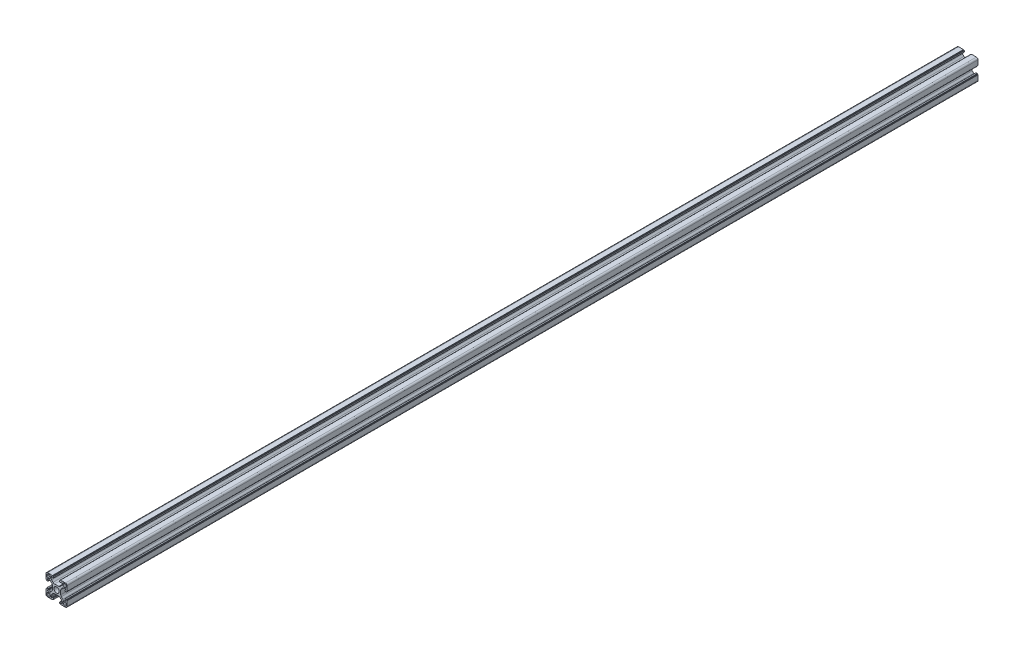
SolidWorks part; units mm, degrees
material "1060 Сплав"
ref_plane "Спереди" through (0, 0, 0) normal (0, 0, 1) x (1, 0, 0)
ref_plane "Сверху" through (0, 0, 0) normal (0, 1, 0) x (1, 0, 0)
ref_plane "Справа" through (0, 0, 0) normal (1, 0, 0) x (0, 0, -1)
sketch "Эскиз2" plane through (0, 0, 0) normal (0, 0, 1) x (1, 0, 0)
  line L0 (9.2299, 9.7837) -> (6.2299, 6.7837) construction
  line L1 (0.1299, 4.6837) -> (2.0286, 4.6837)
  line L2 (0.1299, 0.6837) -> (10.1299, 10.6837) construction
  line L3 (7.7299, 8.2837) -> (6.2299, 9.7837) construction
  line L4 (3.4428, 5.2695) -> (4.7441, 6.5707)
  line L5 (7.0299, 6.7837) -> (8.4299, 6.7837)
  line L6 (6.2299, 7.5837) -> (6.2299, 8.9837)
  line L7 (8.4299, 9.7837) -> (7.0299, 9.7837)
  line L8 (5.3299, 8.8837) -> (5.3299, 7.9849)
  line L9 (3.8931, 8.757) -> (4.3734, 9.2373)
  line L10 (3.3299, 10.2328) -> (3.8299, 10.2328)
  line L11 (3.7163, 8.6837) -> (3.4299, 8.6837)
  line L12 (4.727, 9.3837) -> (4.8299, 9.3837)
  line L13 (3.8299, 10.5337) -> (3.8299, 10.2328)
  line L14 (3.1799, 10.0828) -> (3.1799, 8.9337)
  line L15 (8.6299, 10.6837) -> (3.9799, 10.6837)
  line L16 (9.2299, 8.9837) -> (9.2299, 7.5837)
  line L17 (10.1299, 9.1837) -> (10.1299, 4.5337)
  line L18 (9.5289, 3.7337) -> (8.3799, 3.7337)
  line L19 (9.9799, 4.3837) -> (9.6789, 4.3837)
  line L20 (8.8299, 5.2808) -> (8.8299, 5.3837)
  line L21 (8.1299, 4.2702) -> (8.1299, 3.9837)
  line L22 (9.6789, 3.8837) -> (9.6789, 4.3837)
  line L23 (8.2031, 4.447) -> (8.6834, 4.9273)
  line L24 (8.3299, 5.8837) -> (7.4311, 5.8837)
  line L25 (4.7156, 3.9967) -> (6.0169, 5.2979)
  line L26 (4.1299, 0.6837) -> (4.1299, 2.5825)
  line L27 (4.1299, 0.6837) -> (4.1299, -1.2151)
  line L28 (4.7156, -2.6293) -> (6.0169, -3.9305)
  line L29 (6.2299, -6.2163) -> (6.2299, -7.6163)
  line L30 (7.0299, -5.4163) -> (8.4299, -5.4163)
  line L31 (9.2299, -7.6163) -> (9.2299, -6.2163)
  line L32 (8.3299, -4.5163) -> (7.4311, -4.5163)
  line L33 (8.2031, -3.0795) -> (8.6834, -3.5598)
  line L34 (9.6789, -2.5163) -> (9.6789, -3.0163)
  line L35 (8.1299, -2.9027) -> (8.1299, -2.6163)
  line L36 (8.8299, -3.9134) -> (8.8299, -4.0163)
  line L37 (9.9799, -3.0163) -> (9.6789, -3.0163)
  line L38 (9.5289, -2.3663) -> (8.3799, -2.3663)
  line L39 (10.1299, -7.8163) -> (10.1299, -3.1663)
  line L40 (8.4299, -8.4163) -> (7.0299, -8.4163)
  line L41 (8.6299, -9.3163) -> (3.9799, -9.3163)
  line L42 (3.1799, -8.7153) -> (3.1799, -7.5663)
  line L43 (3.8299, -9.1663) -> (3.8299, -8.8653)
  line L44 (4.727, -8.0163) -> (4.8299, -8.0163)
  line L45 (3.7163, -7.3163) -> (3.4299, -7.3163)
  line L46 (3.3299, -8.8653) -> (3.8299, -8.8653)
  line L47 (3.8931, -7.3895) -> (4.3734, -7.8698)
  line L48 (5.3299, -7.5163) -> (5.3299, -6.6175)
  line L49 (3.4428, -3.9021) -> (4.7441, -5.2033)
  line L50 (0.1299, -3.3163) -> (2.0286, -3.3163)
  line L51 (9.2299, -8.4163) -> (6.2299, -5.4163) construction
  line L52 (0.1299, 0.6837) -> (10.1299, -9.3163) construction
  line L53 (7.7299, -6.9163) -> (9.2299, -5.4163) construction
  line L54 (0.1299, -3.3163) -> (-1.7689, -3.3163)
  line L55 (-3.1831, -3.9021) -> (-4.4844, -5.2033)
  line L56 (-6.7701, -5.4163) -> (-8.1701, -5.4163)
  line L57 (-5.9701, -6.2163) -> (-5.9701, -7.6163)
  line L58 (-8.1701, -8.4163) -> (-6.7701, -8.4163)
  line L59 (-5.0701, -7.5163) -> (-5.0701, -6.6175)
  line L60 (-3.6334, -7.3895) -> (-4.1137, -7.8698)
  line L61 (-3.0701, -8.8653) -> (-3.5701, -8.8653)
  line L62 (-3.4566, -7.3163) -> (-3.1701, -7.3163)
  line L63 (-4.4673, -8.0163) -> (-4.5701, -8.0163)
  line L64 (-3.5701, -9.1663) -> (-3.5701, -8.8653)
  line L65 (-2.9201, -8.7153) -> (-2.9201, -7.5663)
  line L66 (-8.3701, -9.3163) -> (-3.7201, -9.3163)
  line L67 (-8.9701, -7.6163) -> (-8.9701, -6.2163)
  line L68 (-9.8701, -7.8163) -> (-9.8701, -3.1663)
  line L69 (-9.2692, -2.3663) -> (-8.1201, -2.3663)
  line L70 (-9.7201, -3.0163) -> (-9.4192, -3.0163)
  line L71 (-8.5701, -3.9134) -> (-8.5701, -4.0163)
  line L72 (-7.8701, -2.9027) -> (-7.8701, -2.6163)
  line L73 (-9.4192, -2.5163) -> (-9.4192, -3.0163)
  line L74 (-7.9434, -3.0795) -> (-8.4237, -3.5598)
  line L75 (-8.0701, -4.5163) -> (-7.1714, -4.5163)
  line L76 (-4.4559, -2.6293) -> (-5.7572, -3.9305)
  line L77 (-3.8701, 0.6837) -> (-3.8701, -1.2151)
  line L78 (-8.9701, -8.4163) -> (-5.9701, -5.4163) construction
  line L79 (0.1299, 0.6837) -> (-9.8701, -9.3163) construction
  line L80 (-7.4701, -6.9163) -> (-5.9701, -8.4163) construction
  line L81 (-3.8701, 0.6837) -> (-3.8701, 2.5825)
  line L82 (-4.4559, 3.9967) -> (-5.7572, 5.2979)
  line L83 (-5.9701, 7.5837) -> (-5.9701, 8.9837)
  line L84 (-6.7701, 6.7837) -> (-8.1701, 6.7837)
  line L85 (-8.9701, 8.9837) -> (-8.9701, 7.5837)
  line L86 (-8.0701, 5.8837) -> (-7.1714, 5.8837)
  line L87 (-7.9434, 4.447) -> (-8.4237, 4.9273)
  line L88 (-9.4192, 3.8837) -> (-9.4192, 4.3837)
  line L89 (-7.8701, 4.2702) -> (-7.8701, 3.9837)
  line L90 (-8.5701, 5.2808) -> (-8.5701, 5.3837)
  line L91 (-9.7201, 4.3837) -> (-9.4192, 4.3837)
  line L92 (-9.2692, 3.7337) -> (-8.1201, 3.7337)
  line L93 (-9.8701, 9.1837) -> (-9.8701, 4.5337)
  line L94 (-8.1701, 9.7837) -> (-6.7701, 9.7837)
  line L95 (-8.3701, 10.6837) -> (-3.7201, 10.6837)
  line L96 (-2.9201, 10.0828) -> (-2.9201, 8.9337)
  line L97 (-3.5701, 10.5337) -> (-3.5701, 10.2328)
  line L98 (-4.4673, 9.3837) -> (-4.5701, 9.3837)
  line L99 (-3.4566, 8.6837) -> (-3.1701, 8.6837)
  line L100 (-3.0701, 10.2328) -> (-3.5701, 10.2328)
  line L101 (-3.6334, 8.757) -> (-4.1137, 9.2373)
  line L102 (-5.0701, 8.8837) -> (-5.0701, 7.9849)
  line L103 (-3.1831, 5.2695) -> (-4.4844, 6.5707)
  line L104 (0.1299, 4.6837) -> (-1.7689, 4.6837)
  line L105 (-11.6342, 0.6837) -> (11.6342, 0.6837) construction
  line L106 (-8.9701, 9.7837) -> (-5.9701, 6.7837) construction
  line L107 (0.1299, -11.4027) -> (0.1299, 11.4027) construction
  line L108 (0.1299, 0.6837) -> (-9.8701, 10.6837) construction
  line L109 (-7.4701, 8.2837) -> (-8.9701, 6.7837) construction
  arc A0 (9.2299, 8.9837) -> (8.4299, 9.7837) centre (8.4299, 8.9837) ccw
  arc A1 (7.0299, 9.7837) -> (6.2299, 8.9837) centre (7.0299, 8.9837) ccw
  arc A2 (7.0299, 6.7837) -> (6.2299, 7.5837) centre (7.0299, 7.5837) cw
  arc A3 (8.6299, 10.6837) -> (10.1299, 9.1837) centre (8.6299, 9.1837) cw
  arc A4 (3.3299, 10.2328) -> (3.1799, 10.0828) centre (3.3299, 10.0828) ccw
  arc A5 (3.9799, 10.6837) -> (3.8299, 10.5337) centre (3.9799, 10.5337) ccw
  arc A6 (3.7163, 8.6837) -> (3.8931, 8.757) centre (3.7163, 8.9337) ccw
  arc A7 (3.4299, 8.6837) -> (3.1799, 8.9337) centre (3.4299, 8.9337) cw
  arc A8 (4.3734, 9.2373) -> (4.727, 9.3837) centre (4.727, 8.8837) cw
  arc A9 (4.8299, 9.3837) -> (5.3299, 8.8837) centre (4.8299, 8.8837) cw
  arc A10 (2.6299, 0.6837) -> (0.1299, 3.1837) centre (0.1299, 0.6837) ccw
  arc A11 (2.0286, 4.6837) -> (3.4428, 5.2695) centre (2.0286, 6.6837) ccw
  arc A12 (5.3299, 7.9849) -> (4.7441, 6.5707) centre (3.3299, 7.9849) cw
  arc A13 (9.2299, 7.5837) -> (8.4299, 6.7837) centre (8.4299, 7.5837) cw
  arc A14 (8.8299, 5.3837) -> (8.3299, 5.8837) centre (8.3299, 5.3837) ccw
  arc A15 (8.6834, 4.9273) -> (8.8299, 5.2808) centre (8.3299, 5.2808) ccw
  arc A16 (8.1299, 3.9837) -> (8.3799, 3.7337) centre (8.3799, 3.9837) ccw
  arc A17 (8.1299, 4.2702) -> (8.2031, 4.447) centre (8.3799, 4.2702) cw
  arc A18 (10.1299, 4.5337) -> (9.9799, 4.3837) centre (9.9799, 4.5337) cw
  arc A19 (9.6789, 3.8837) -> (9.5289, 3.7337) centre (9.5289, 3.8837) cw
  arc A20 (7.4311, 5.8837) -> (6.0169, 5.2979) centre (7.4311, 3.8837) ccw
  arc A21 (4.1299, 2.5825) -> (4.7156, 3.9967) centre (6.1299, 2.5825) cw
  arc A22 (8.4299, -8.4163) -> (9.2299, -7.6163) centre (8.4299, -7.6163) ccw
  arc A23 (9.2299, -6.2163) -> (8.4299, -5.4163) centre (8.4299, -6.2163) ccw
  arc A24 (6.2299, -6.2163) -> (7.0299, -5.4163) centre (7.0299, -6.2163) cw
  arc A25 (10.1299, -7.8163) -> (8.6299, -9.3163) centre (8.6299, -7.8163) cw
  arc A26 (9.6789, -2.5163) -> (9.5289, -2.3663) centre (9.5289, -2.5163) ccw
  arc A27 (10.1299, -3.1663) -> (9.9799, -3.0163) centre (9.9799, -3.1663) ccw
  arc A28 (8.1299, -2.9027) -> (8.2031, -3.0795) centre (8.3799, -2.9027) ccw
  arc A29 (8.1299, -2.6163) -> (8.3799, -2.3663) centre (8.3799, -2.6163) cw
  arc A30 (8.6834, -3.5598) -> (8.8299, -3.9134) centre (8.3299, -3.9134) cw
  arc A31 (8.8299, -4.0163) -> (8.3299, -4.5163) centre (8.3299, -4.0163) cw
  arc A32 (0.1299, -1.8163) -> (2.6299, 0.6837) centre (0.1299, 0.6837) ccw
  arc A33 (4.1299, -1.2151) -> (4.7156, -2.6293) centre (6.1299, -1.2151) ccw
  arc A34 (7.4311, -4.5163) -> (6.0169, -3.9305) centre (7.4311, -2.5163) cw
  arc A35 (7.0299, -8.4163) -> (6.2299, -7.6163) centre (7.0299, -7.6163) cw
  arc A36 (4.8299, -8.0163) -> (5.3299, -7.5163) centre (4.8299, -7.5163) ccw
  arc A37 (4.3734, -7.8698) -> (4.727, -8.0163) centre (4.727, -7.5163) ccw
  arc A38 (3.4299, -7.3163) -> (3.1799, -7.5663) centre (3.4299, -7.5663) ccw
  arc A39 (3.7163, -7.3163) -> (3.8931, -7.3895) centre (3.7163, -7.5663) cw
  arc A40 (3.9799, -9.3163) -> (3.8299, -9.1663) centre (3.9799, -9.1663) cw
  arc A41 (3.3299, -8.8653) -> (3.1799, -8.7153) centre (3.3299, -8.7153) cw
  arc A42 (5.3299, -6.6175) -> (4.7441, -5.2033) centre (3.3299, -6.6175) ccw
  arc A43 (2.0286, -3.3163) -> (3.4428, -3.9021) centre (2.0286, -5.3163) cw
  arc A44 (-8.9701, -7.6163) -> (-8.1701, -8.4163) centre (-8.1701, -7.6163) ccw
  arc A45 (-6.7701, -8.4163) -> (-5.9701, -7.6163) centre (-6.7701, -7.6163) ccw
  arc A46 (-6.7701, -5.4163) -> (-5.9701, -6.2163) centre (-6.7701, -6.2163) cw
  arc A47 (-8.3701, -9.3163) -> (-9.8701, -7.8163) centre (-8.3701, -7.8163) cw
  arc A48 (-3.0701, -8.8653) -> (-2.9201, -8.7153) centre (-3.0701, -8.7153) ccw
  arc A49 (-3.7201, -9.3163) -> (-3.5701, -9.1663) centre (-3.7201, -9.1663) ccw
  arc A50 (-3.4566, -7.3163) -> (-3.6334, -7.3895) centre (-3.4566, -7.5663) ccw
  arc A51 (-3.1701, -7.3163) -> (-2.9201, -7.5663) centre (-3.1701, -7.5663) cw
  arc A52 (-4.1137, -7.8698) -> (-4.4673, -8.0163) centre (-4.4673, -7.5163) cw
  arc A53 (-4.5701, -8.0163) -> (-5.0701, -7.5163) centre (-4.5701, -7.5163) cw
  arc A54 (-2.3701, 0.6837) -> (0.1299, -1.8163) centre (0.1299, 0.6837) ccw
  arc A55 (-1.7689, -3.3163) -> (-3.1831, -3.9021) centre (-1.7689, -5.3163) ccw
  arc A56 (-5.0701, -6.6175) -> (-4.4844, -5.2033) centre (-3.0701, -6.6175) cw
  arc A57 (-8.9701, -6.2163) -> (-8.1701, -5.4163) centre (-8.1701, -6.2163) cw
  arc A58 (-8.5701, -4.0163) -> (-8.0701, -4.5163) centre (-8.0701, -4.0163) ccw
  arc A59 (-8.4237, -3.5598) -> (-8.5701, -3.9134) centre (-8.0701, -3.9134) ccw
  arc A60 (-7.8701, -2.6163) -> (-8.1201, -2.3663) centre (-8.1201, -2.6163) ccw
  arc A61 (-7.8701, -2.9027) -> (-7.9434, -3.0795) centre (-8.1201, -2.9027) cw
  arc A62 (-9.8701, -3.1663) -> (-9.7201, -3.0163) centre (-9.7201, -3.1663) cw
  arc A63 (-9.4192, -2.5163) -> (-9.2692, -2.3663) centre (-9.2692, -2.5163) cw
  arc A64 (-7.1714, -4.5163) -> (-5.7572, -3.9305) centre (-7.1714, -2.5163) ccw
  arc A65 (-3.8701, -1.2151) -> (-4.4559, -2.6293) centre (-5.8701, -1.2151) cw
  arc A66 (-8.1701, 9.7837) -> (-8.9701, 8.9837) centre (-8.1701, 8.9837) ccw
  arc A67 (-8.9701, 7.5837) -> (-8.1701, 6.7837) centre (-8.1701, 7.5837) ccw
  arc A68 (-5.9701, 7.5837) -> (-6.7701, 6.7837) centre (-6.7701, 7.5837) cw
  arc A69 (-9.8701, 9.1837) -> (-8.3701, 10.6837) centre (-8.3701, 9.1837) cw
  arc A70 (-9.4192, 3.8837) -> (-9.2692, 3.7337) centre (-9.2692, 3.8837) ccw
  arc A71 (-9.8701, 4.5337) -> (-9.7201, 4.3837) centre (-9.7201, 4.5337) ccw
  arc A72 (-7.8701, 4.2702) -> (-7.9434, 4.447) centre (-8.1201, 4.2702) ccw
  arc A73 (-7.8701, 3.9837) -> (-8.1201, 3.7337) centre (-8.1201, 3.9837) cw
  arc A74 (-8.4237, 4.9273) -> (-8.5701, 5.2808) centre (-8.0701, 5.2808) cw
  arc A75 (-8.5701, 5.3837) -> (-8.0701, 5.8837) centre (-8.0701, 5.3837) cw
  arc A76 (0.1299, 3.1837) -> (-2.3701, 0.6837) centre (0.1299, 0.6837) ccw
  arc A77 (-3.8701, 2.5825) -> (-4.4559, 3.9967) centre (-5.8701, 2.5825) ccw
  arc A78 (-7.1714, 5.8837) -> (-5.7572, 5.2979) centre (-7.1714, 3.8837) cw
  arc A79 (-6.7701, 9.7837) -> (-5.9701, 8.9837) centre (-6.7701, 8.9837) cw
  arc A80 (-4.5701, 9.3837) -> (-5.0701, 8.8837) centre (-4.5701, 8.8837) ccw
  arc A81 (-4.1137, 9.2373) -> (-4.4673, 9.3837) centre (-4.4673, 8.8837) ccw
  arc A82 (-3.1701, 8.6837) -> (-2.9201, 8.9337) centre (-3.1701, 8.9337) ccw
  arc A83 (-3.4566, 8.6837) -> (-3.6334, 8.757) centre (-3.4566, 8.9337) cw
  arc A84 (-3.7201, 10.6837) -> (-3.5701, 10.5337) centre (-3.7201, 10.5337) cw
  arc A85 (-3.0701, 10.2328) -> (-2.9201, 10.0828) centre (-3.0701, 10.0828) cw
  arc A86 (-5.0701, 7.9849) -> (-4.4844, 6.5707) centre (-3.0701, 7.9849) ccw
  arc A87 (-1.7689, 4.6837) -> (-3.1831, 5.2695) centre (-1.7689, 6.6837) cw
  point P0 (0.1299, 0.6837)
  point P9 (0.1299, 0.6837)
  point P40 (8.8299, 4.3837)
  point P93 (3.8299, -8.0163)
  point P144 (3.8299, 9.3837)
  point P152 (8.8299, -3.0163)
  point P153 (0.1299, -3.2405)
  point P154 (0.1299, 0.6837)
  point P189 (-8.5701, -3.0163)
  point P228 (-3.5701, -8.0163)
  point P229 (-3.7944, 0.6837)
  point P230 (0.1299, 0.6837)
  point P268 (-3.5701, 9.3837)
  point P273 (4.0541, 0.6837)
  point P306 (-8.5701, 4.3837)
  point P307 (0.1299, 4.608)
  point P309 (0.1299, 0.6837)
  dimension "D3" = 5
  dimension "D6" = 2
  dimension "D1" = 2
  dimension "D2" = 6
  dimension "D4" = 4
  dimension "D5" = 0.9
extrude "Бобышка-Вытянуть1" add sketch "Эскиз2" along normal blind 865
